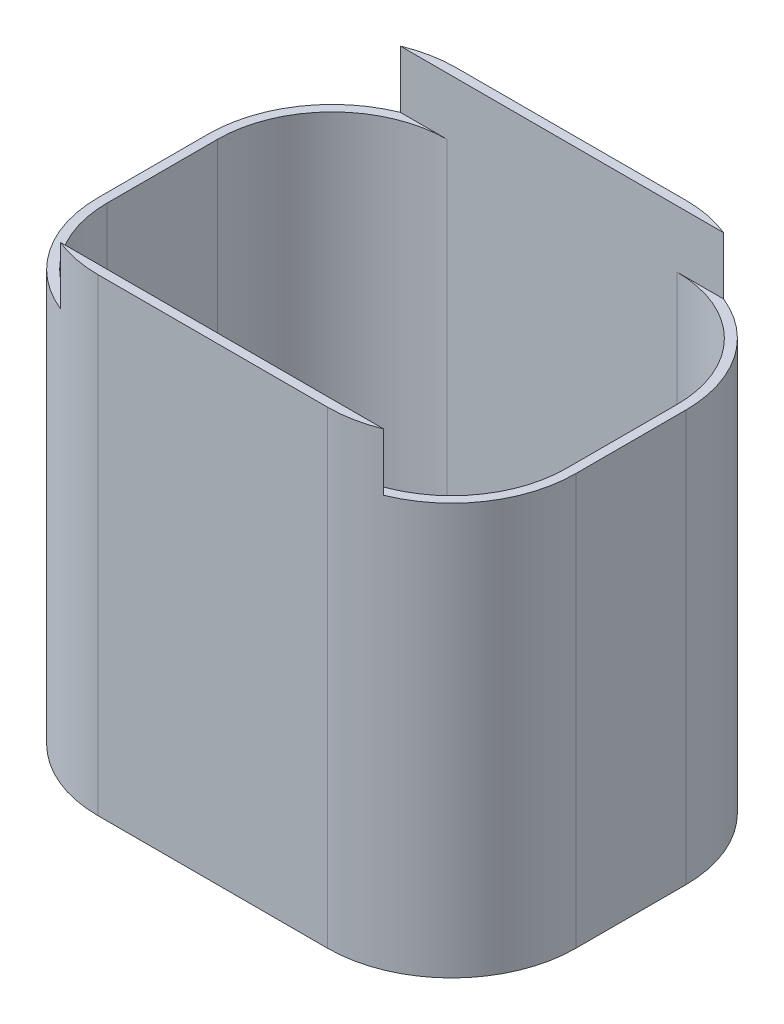
SolidWorks part; units mm, degrees
ref_plane "前基準面" through (0, 0, 0) normal (0, 0, 1) x (1, 0, 0)
ref_plane "上基準面" through (0, 0, 0) normal (0, 1, 0) x (1, 0, 0)
ref_plane "右基準面" through (0, 0, 0) normal (1, 0, 0) x (0, 0, -1)
sketch "草圖1" plane through (0, 0, 0) normal (0, 1, 0) x (1, 0, 0)
  line L0 (-10, -15.6) -> (10, -15.6)
  line L1 (-10, -14.8) -> (10, -14.8)
  line L2 (-20, -4.8) -> (-20, 4.8)
  line L3 (-10, 14.8) -> (10, 14.8)
  line L4 (20, -4.8) -> (20, 4.8)
  line L5 (-20, -14.8) -> (20, 14.8) construction
  line L6 (-20, 14.8) -> (20, -14.8) construction
  line L7 (20.8, -4.8) -> (20.8, 4.8)
  line L8 (-10, 15.6) -> (10, 15.6)
  line L9 (-20.8, -4.8) -> (-20.8, 4.8)
  arc A0 (-20, 4.8) -> (-10, 14.8) centre (-10, 4.8) cw
  arc A1 (10, 14.8) -> (20, 4.8) centre (10, 4.8) cw
  arc A2 (20, -4.8) -> (10, -14.8) centre (10, -4.8) cw
  arc A3 (-10, -14.8) -> (-20, -4.8) centre (-10, -4.8) cw
  arc A4 (20.8, -4.8) -> (10, -15.6) centre (10, -4.8) cw
  arc A5 (10, 15.6) -> (20.8, 4.8) centre (10, 4.8) cw
  arc A6 (-20.8, 4.8) -> (-10, 15.6) centre (-10, 4.8) cw
  arc A7 (-10, -15.6) -> (-20.8, -4.8) centre (-10, -4.8) cw
  point P0 (0, 0)
  dimension "D3" = 10
  dimension "D4" = 10
  dimension "D1" = 40
  dimension "D2" = 29.6
  dimension "D5" = 0.8
extrude "填料-伸長1" add sketch "草圖1" along normal blind 40.8
sketch "草圖4" plane through (0, 40.8, 0) normal (0, 1, 0) x (1, 0, 0)
  line L0 (10, 14.8) -> (-10, 14.8) construction
  line L1 (-20.8, -14.8) -> (20.8, -14.8)
  line L2 (-20.8, -14.8) -> (-20.8, 14.8)
  line L3 (-20.8, 14.8) -> (20.8, 14.8)
  line L4 (20.8, -14.8) -> (20.8, 14.8)
  line L5 (-20.8, -14.8) -> (20.8, 14.8) construction
  line L6 (-20.8, 14.8) -> (20.8, -14.8) construction
  line L8 (-20.8, 4.8) -> (-20.8, -4.8) construction
  point P0 (0, 0)
  point P8 (-20.8, 0)
extrude "除料-伸長1" cut sketch "草圖4" against normal blind 5
sketch "草圖5" plane through (0, 0, 0) normal (0, -1, 0) x (1, 0, 0)
  line L0 (20, 4.8) -> (20, -4.8) construction
  line L1 (-10, 14.8) -> (10, 14.8) construction
  line L2 (10, -14.8) -> (-10, -14.8) construction
  line L3 (-20, -4.8) -> (-20, 4.8) construction
  line L4 (20, 4.8) -> (20, -4.8)
  line L5 (-10, 14.8) -> (10, 14.8)
  line L6 (10, -14.8) -> (-10, -14.8)
  line L7 (-20, -4.8) -> (-20, 4.8)
  arc A0 (20, 4.8) -> (10, 14.8) centre (10, 4.8) ccw construction
  arc A1 (10, -14.8) -> (20, -4.8) centre (10, -4.8) ccw construction
  arc A2 (-20, -4.8) -> (-10, -14.8) centre (-10, -4.8) ccw construction
  arc A3 (-10, 14.8) -> (-20, 4.8) centre (-10, 4.8) ccw construction
  arc A4 (20, 4.8) -> (10, 14.8) centre (10, 4.8) ccw
  arc A5 (10, -14.8) -> (20, -4.8) centre (10, -4.8) ccw
  arc A6 (-20, -4.8) -> (-10, -14.8) centre (-10, -4.8) ccw
  arc A7 (-10, 14.8) -> (-20, 4.8) centre (-10, 4.8) ccw
extrude "填料-伸長2" add sketch "草圖5" against normal blind 0.8
sketch "草圖7" plane through (0, 0, 0) normal (0, -1, 0) x (1, 0, 0)
  line L0 (0, 14.8) -> (0, 0) construction
  line L1 (10, 14.8) -> (-10, 14.8) construction
  line L2 (-10, -14.8) -> (10, -14.8) construction
  line L3 (-20, 0) -> (-7.4, 0) construction
  line L4 (-20, 4.8) -> (-20, -4.8) construction
  line L5 (20, -4.8) -> (20, 4.8) construction
  line L6 (-7.4, 7.1) -> (-7.4, -7.1)
  line L7 (7.4, 7.1) -> (7.4, -7.1)
  line L8 (7.4, 0) -> (20, 0) construction
  line L9 (0, -14.5) -> (0, -14.8) construction
  arc A0 (7.4, 7.1) -> (-7.4, 7.1) centre (0, 7.1) ccw
  arc A1 (-7.4, -7.1) -> (7.4, -7.1) centre (0, -7.1) ccw
  point P20 (0, 0)
  point P23 (0, 14.8)
  point P24 (0, 14.8)
  point P25 (0, 14.8)
  dimension "D2" = 14.8
  dimension "D1" = 14.2
extrude "除料-伸長2" cut sketch "草圖7" against normal through all
